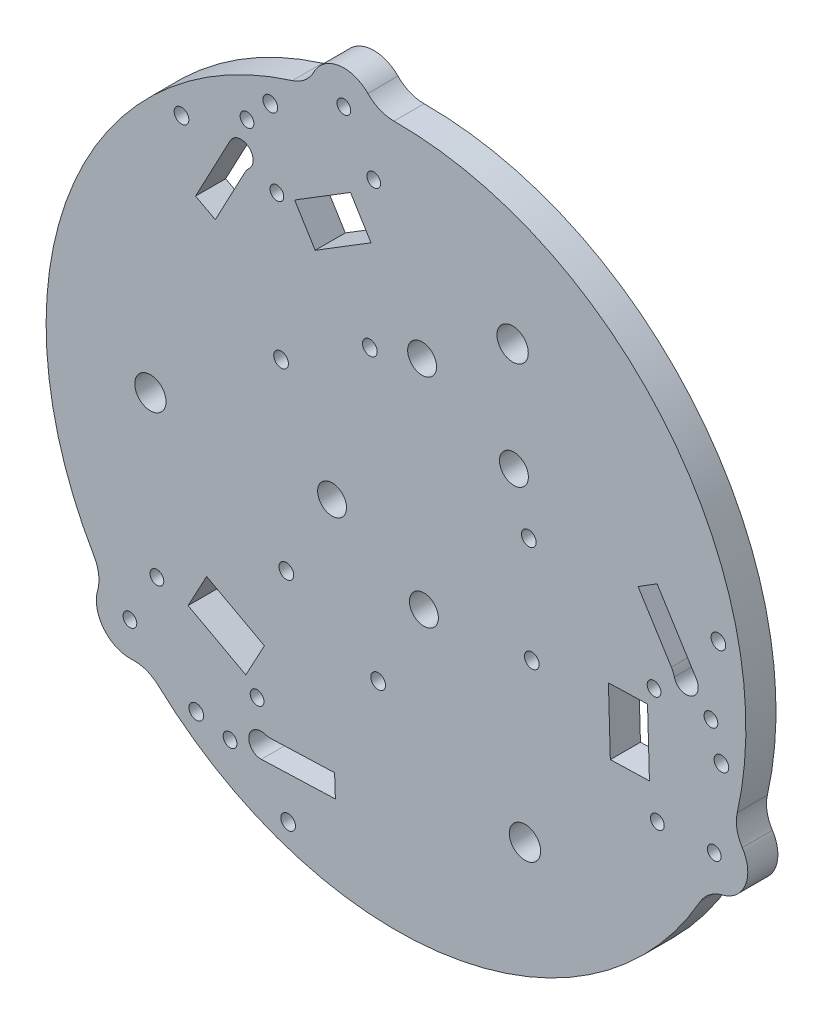
SolidWorks part; units mm, degrees
material "Acrylic (Medium-high impact)"
ref_plane "Front Plane" through (0, 0, 0) normal (0, 0, 1) x (1, 0, 0)
ref_plane "Top Plane" through (0, 0, 0) normal (0, 1, 0) x (1, 0, 0)
ref_plane "Right Plane" through (0, 0, 0) normal (1, 0, 0) x (0, 0, -1)
sketch "Model" plane through (0, 0, 0) normal (0, 0, 1) x (1, 0, 0)
  line L0 (-34.9479, 52.9765) -> (-42.2731, 39.1655)
  line L1 (-38.0994, 36.9519) -> (-42.2731, 39.1655)
  line L2 (-31.9031, 48.6345) -> (-38.0994, 36.9519)
  line L3 (63.353, 3.7775) -> (55.0549, 17.0268)
  line L4 (51.051, 14.5191) -> (55.0549, 17.0268)
  line L5 (58.0702, 3.3116) -> (51.051, 14.5191)
  line L6 (-28.4051, -56.754) -> (-12.7818, -56.1923)
  line L7 (-12.9515, -51.471) -> (-12.7818, -56.1923)
  line L8 (-26.1672, -51.9461) -> (-12.9515, -51.471)
  line L9 (53.0434, -5.9454) -> (44.7956, -6.1849)
  line L10 (44.7956, -6.1849) -> (45.1971, -20.0123)
  line L11 (45.1971, -20.0123) -> (53.4449, -19.7728)
  line L12 (53.4449, -19.7728) -> (53.0434, -5.9454)
  line L13 (-21.3728, 48.9096) -> (-17.0415, 41.8865)
  line L14 (-17.0415, 41.8865) -> (-5.2674, 49.148)
  line L15 (-5.2674, 49.148) -> (-9.5987, 56.171)
  line L16 (-9.5987, 56.171) -> (-21.3728, 48.9096)
  line L17 (-31.6705, -42.9642) -> (-27.754, -35.7016)
  line L18 (-27.754, -35.7016) -> (-39.9297, -29.1357)
  line L19 (-39.9297, -29.1357) -> (-43.8462, -36.3982)
  line L20 (-43.8462, -36.3982) -> (-31.6705, -42.9642)
  circle A0 centre (-10.9945, 71.1462) radius 1.45
  circle A1 centre (-56.1171, -45.0946) radius 1.45
  circle A2 centre (-4.6954, 60.9324) radius 1.45
  circle A3 centre (-31.4221, 58.548) radius 1.45
  circle A4 centre (-25.123, 48.3342) radius 1.45
  circle A5 centre (-50.4213, -34.5326) radius 1.45
  circle A6 centre (-34.993, -56.4863) radius 1.45
  circle A7 centre (-29.2972, -45.9242) radius 1.45
  circle A8 centre (67.1117, -26.0516) radius 1.45
  circle A9 centre (-24.2354, 18.3415) radius 1.55
  circle A10 centre (-5.5102, 29.8899) radius 1.55
  circle A11 centre (-26.5072, 63.9358) radius 1.55
  circle A12 centre (-45.2325, 52.3874) radius 1.55
  circle A13 centre (-22.7526, -65.3662) radius 1.55
  circle A14 centre (-42.1164, -54.9238) radius 1.55
  circle A15 centre (-3.7665, -30.1592) radius 1.55
  circle A16 centre (-23.1303, -19.7169) radius 1.55
  circle A17 centre (28.0019, 11.8177) radius 1.55
  circle A18 centre (28.6405, -10.173) radius 1.55
  circle A19 centre (68.6236, -9.012) radius 1.55
  circle A20 centre (67.985, 12.9788) radius 1.55
  circle A21 centre (27.1996, -44.1031) radius 3.3
  circle A22 centre (24.5946, 45.6071) radius 3.3
  circle A23 centre (-51.7942, -1.504) radius 3.3
  circle A24 centre (-13.4808, -1.8233) radius 3.048
  circle A25 centre (5.883, -12.2657) radius 3.048
  circle A26 centre (24.8691, 22.9412) radius 3.048
  circle A27 centre (5.5053, 33.3836) radius 3.048
  circle A28 centre (54.4201, -2.41) radius 1.45
  circle A29 centre (66.4151, -2.0617) radius 1.45
  circle A30 centre (55.1167, -26.3999) radius 1.45
  arc A31 (-30.923, 49.9287) -> (-31.9031, 48.6345) centre (-27.4153, 46.2542) ccw
  arc A32 (-30.923, 49.9287) -> (-34.9479, 52.9765) centre (-32.6888, 51.7783) ccw
  arc A33 (71.9631, -16.3043) -> (73.0248, -22.1698) centre (79.3948, -17.988) ccw
  arc A34 (68.8571, -32.9062) -> (73.0248, -22.1698) centre (67.1117, -26.0516) ccw
  arc A35 (68.8571, -32.9062) -> (64.116, -36.5192) centre (70.7373, -40.2906) ccw
  arc A36 (-50.1015, -54.1698) -> (-55.712, -52.1564) centre (-55.2755, -59.7639) ccw
  arc A37 (-62.9261, -43.1788) -> (-55.712, -52.1564) centre (-56.1171, -45.0946) ccw
  arc A38 (-62.9261, -43.1788) -> (-63.6846, -37.2665) centre (-70.2613, -41.115) ccw
  arc A39 (-21.8617, 70.474) -> (-17.3128, 74.3262) centre (-24.1193, 77.7519) ccw
  arc A40 (-5.9309, 76.0851) -> (-17.3128, 74.3262) centre (-10.9945, 71.1462) ccw
  arc A41 (-5.9309, 76.0851) -> (-0.4314, 73.7857) centre (-0.476, 81.4056) ccw
  arc A42 (71.9631, -16.3043) -> (-0.4314, 73.7857) centre (0, 0) ccw
  arc A43 (58.701, 1.8158) -> (58.0702, 3.3116) centre (53.7649, 0.6152) ccw
  arc A44 (58.701, 1.8158) -> (63.353, 3.7775) centre (61.1858, 2.4202) ccw
  arc A45 (-27.778, -51.7445) -> (-26.1672, -51.9461) centre (-26.3497, -46.8694) ccw
  arc A46 (-27.778, -51.7445) -> (-28.4051, -56.754) centre (-28.497, -54.1985) ccw
  arc A47 (-50.1015, -54.1698) -> (64.116, -36.5192) centre (0, 0) ccw
  arc A48 (-21.8617, 70.474) -> (-63.6846, -37.2665) centre (0, 0) ccw
extrude "Boss-Extrude1" add sketch "Model" along normal blind 6.35
